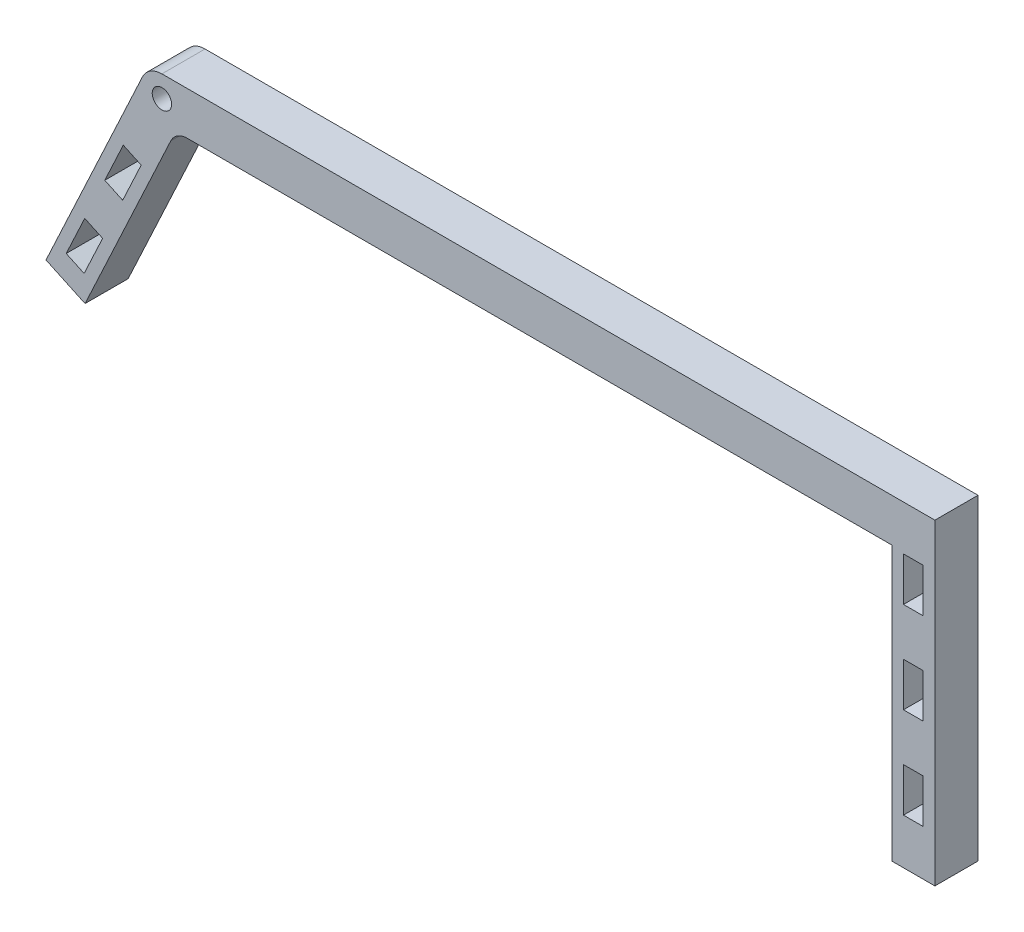
SolidWorks part; units mm, degrees
ref_plane "Front Plane" through (0, 0, 0) normal (0, 0, 1) x (1, 0, 0)
ref_plane "Top Plane" through (0, 0, 0) normal (0, 1, 0) x (1, 0, 0)
ref_plane "Right Plane" through (0, 0, 0) normal (1, 0, 0) x (0, 0, -1)
sketch "Sketch1" plane through (0, 0, 0) normal (0, 0, 1) x (1, 0, 0)
  line L0 (-50.3888, -3) -> (-62.9992, -30.0431)
  line L1 (-50.3888, -3) -> (55.3, -3)
  line L2 (-55.3, 0.6651) -> (-55.3, 3) construction
  line L3 (-52.3, 3) -> (55.3, 3)
  line L5 (-55.3, -3) -> (55.3, 3) construction
  line L6 (-55.3, 3) -> (55.3, -3) construction
  line L8 (55.3, 3) -> (55.3, -41.1)
  line L9 (55.3, -41.1) -> (49.3, -41.1)
  line L10 (49.3, 3) -> (49.3, -41.1)
  line L11 (-55.3, 0.6651) -> (-68.4371, -27.5074)
  line L12 (-68.4371, -27.5074) -> (-62.9992, -30.0431)
  line L13 (-55.3, 3) -> (-52.3, 3) construction
  line L14 (-55.3, -3) -> (-52.3, -3) construction
  line L15 (-52.3, -3) -> (-50.3888, -3) construction
  line L16 (-55.3, -3) -> (-55.3, 0) construction
  line L17 (-55.3, 0) -> (-55.3, 0.6651) construction
  line L18 (-55.3, 0.6651) -> (-55.0189, 1.2679)
  circle A0 centre (-52.3, 0) radius 1.35
  arc A2 (-52.3, 3) -> (-55.0189, 1.2679) centre (-52.3, 0) ccw
  arc A3 (-55.0189, 1.2679) -> (-55.3, 0) centre (-52.3, 0) ccw construction
  arc A4 (-55.3, 0) -> (-53.1318, -2.8824) centre (-52.3, 0) ccw construction
  arc A5 (-53.1318, -2.8824) -> (-52.3, -3) centre (-52.3, 0) ccw construction
  arc A6 (-52.3, -3) -> (-51.1613, -2.7755) centre (-52.3, 0) ccw construction
  arc A7 (-51.1613, -2.7755) -> (-53.1318, 2.8824) centre (-52.3, 0) ccw construction
  arc A8 (-53.1318, 2.8824) -> (-52.3, 3) centre (-52.3, 0) ccw construction
  point P0 (0, 0)
  point P22 (0, 0)
  point P23 (-42.0349, 0.6832)
  point P24 (-57.3727, -30.0431)
  dimension "D5" = 2.7
  dimension "D1" = 6
  dimension "D2" = 101.6
  dimension "D3" = 44.1
  dimension "D4" = 6
  dimension "D6" = 115
  dimension "D7" = 3
  dimension "D8" = 3
  dimension "D9" = 6
  dimension "D10" = 31.75
extrude "Boss-Extrude1" add sketch "Sketch1" along normal mid plane 6
fillet "Fillet1" radius 2.54 1 edges at (-50.3888, -3, 0)
sketch "Sketch2" plane through (0, 0, 3) normal (0, 0, 1) x (1, 0, 0)
  line L0 (-63.0462, -19.7918) -> (-65.6225, -25.3166)
  line L1 (-63.0462, -19.7918) -> (-60.5539, -20.954)
  line L2 (-65.6225, -25.3166) -> (-63.1301, -26.4788)
  line L3 (-60.5539, -20.954) -> (-63.1301, -26.4788)
  line L4 (-68.4371, -27.5074) -> (-55.0189, 1.2679) construction
  line L5 (-68.4371, -27.5074) -> (-62.9992, -30.0431) construction
  line L6 (-51.0727, -4.4665) -> (-62.9992, -30.0431) construction
  point P10 (-64.3763, -25.8977)
  dimension "D1" = 2.75
  dimension "D2" = 6.096
  dimension "D3" = 3.175
  dimension "D4" = 3
extrude "Cut-Extrude1" cut sketch "Sketch2" against normal through all both and the other way through all
pattern_linear "LPattern1" count 2 spacing 12.7 along (0.4226, 0.9063, 0) of "Cut-Extrude1"
sketch "Sketch3" plane through (0, 0, 3) normal (0, 0, 1) x (1, 0, 0)
  line L0 (55.3, -41.1) -> (49.3, -41.1) construction
  line L1 (50.925, -28.654) -> (53.675, -28.654)
  line L2 (50.925, -28.654) -> (50.925, -34.75)
  line L3 (50.925, -34.75) -> (53.675, -34.75)
  line L4 (53.675, -28.654) -> (53.675, -34.75)
  line L5 (49.3, -3) -> (49.3, -41.1) construction
  point P6 (52.3, -34.75)
  dimension "D1" = 2.75
  dimension "D2" = 6.096
  dimension "D3" = 6.35
  dimension "D4" = 3
extrude "Cut-Extrude2" cut sketch "Sketch3" against normal through all both and the other way through all
pattern_linear "LPattern2" count 3 spacing 12.7 along (0, 1, 0) of "Cut-Extrude2"
